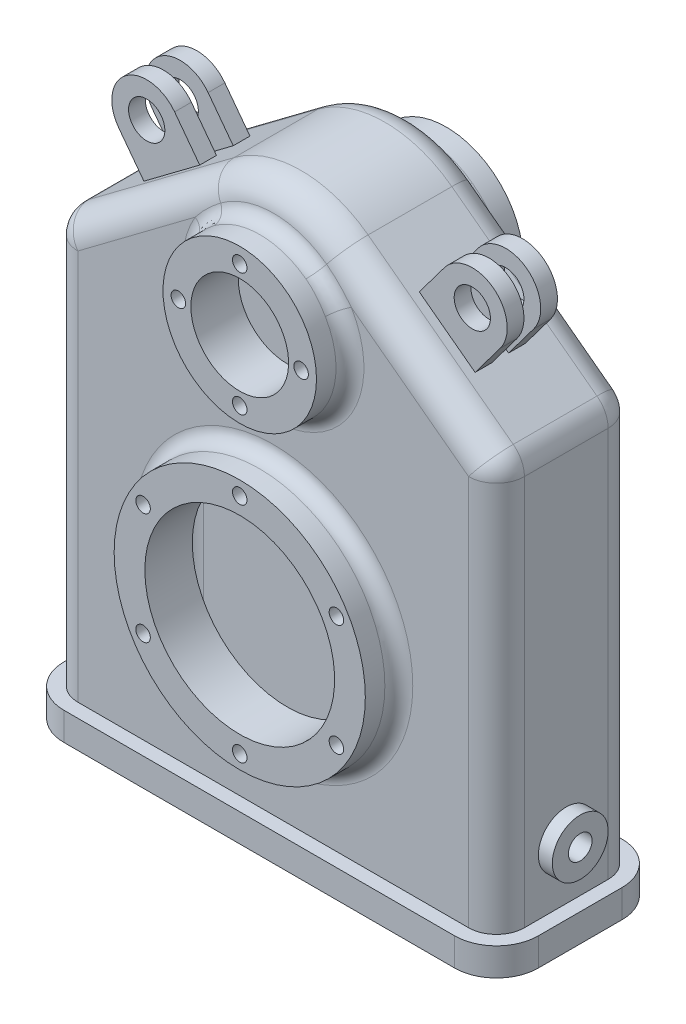
SolidWorks part; units mm, degrees
ref_plane "Front Plane" through (0, 0, 0) normal (0, 0, 1) x (1, 0, 0)
ref_plane "Top Plane" through (0, 0, 0) normal (0, 1, 0) x (1, 0, 0)
ref_plane "Right Plane" through (0, 0, 0) normal (1, 0, 0) x (0, 0, -1)
sketch "Sketch1" plane through (0, 0, 0) normal (0, 1, 0) x (1, 0, 0)
  line L1 (15, 0) -> (155, 0)
  line L2 (0, 15) -> (0, 45)
  line L3 (15, 60) -> (155, 60)
  line L4 (170, 15) -> (170, 45)
  arc A0 (155, 0) -> (170, 15) centre (155, 15) ccw
  arc A1 (0, 45) -> (15, 60) centre (15, 45) cw
  arc A2 (155, 60) -> (170, 45) centre (155, 45) cw
  arc A3 (15, 0) -> (0, 15) centre (15, 15) cw
  point P7 (170, 0)
  point P10 (0, 60)
  point P15 (0, 0)
  dimension "D3" = 15
  dimension "D1" = 170
  dimension "D2" = 60
extrude "Boss-Extrude1" add sketch "Sketch1" along normal blind 10
ref_plane "Plane1" through (0, 0, -30) normal (0, 0, 1) x (1, 0, 0)
sketch "Sketch2" plane through (0, 0, -30) normal (0, 0, 1) x (1, 0, 0)
  line L0 (5, 10) -> (165, 10)
  line L1 (15, 10) -> (0, 10) construction
  line L2 (170, 10) -> (155, 10) construction
  line L3 (165, 10) -> (165, 150)
  line L5 (5, 150) -> (5, 10)
  line L6 (0, 10) -> (0, 0) construction
  line L7 (9, 158) -> (61, 197)
  line L8 (109, 197) -> (161, 158)
  arc A0 (109, 197) -> (61, 197) centre (85, 165) ccw
  arc A1 (165, 150) -> (161, 158) centre (155, 150) ccw
  arc A2 (5, 150) -> (9, 158) centre (15, 150) cw
  point P12 (0, 0)
  point P20 (0, 0)
  dimension "D3" = 80
  dimension "D6" = 10
  dimension "D1" = 160
  dimension "D2" = 5
  dimension "D4" = 165
  dimension "D5" = 85
  dimension "D7" = 150
extrude "Boss-Extrude2" add sketch "Sketch2" along normal mid plane 50
fillet "Fillet1" radius 10 14 edges at (165, 80, -55) (163.9443, 154.4721, -55) (135, 177.5, -55) (85, 205, -55) (35, 177.5, -55) (6.0557, 154.4721, -55) (165, 80, -5) (163.9443, 154.4721, -5) (135, 177.5, -5) (85, 205, -5) (35, 177.5, -5) (6.0557, 154.4721, -5) (5, 80, -55) (5, 80, -5)
sketch "Sketch3" plane through (0, 0, -30) normal (0, 0, 1) x (1, 0, 0)
  line L0 (10, 0) -> (10, 150)
  line L1 (0, 0) -> (15, 0) construction
  line L3 (160, 150) -> (160, 0)
  line L4 (155, 0) -> (170, 0) construction
  line L5 (160, 0) -> (10, 0)
  line L6 (165, 10) -> (165, 150) construction
  line L7 (5, 150) -> (5, 10) construction
  line L8 (12, 154) -> (64, 193)
  line L9 (106, 193) -> (158, 154)
  line L10 (161, 158) -> (109, 197) construction
  arc A0 (106, 193) -> (64, 193) centre (85, 165) ccw
  arc A1 (158, 154) -> (160, 150) centre (155, 150) cw
  arc A2 (103, 189) -> (67, 189) centre (85, 165) ccw construction
  arc A3 (10, 150) -> (12, 154) centre (15, 150) cw
  point P1 (0, 0)
  point P25 (0, 0)
  dimension "D1" = 70
  dimension "D4" = 5
  dimension "D2" = 5
  dimension "D3" = 5
extrude "Cut-Extrude1" cut sketch "Sketch3" against normal mid plane 40
sketch "Sketch4" plane through (0, 0, -5) normal (0, 0, 1) x (1, 0, 0)
  circle A0 centre (85, 165) radius 27.5
  circle A1 centre (85, 75) radius 45
  point P4 (0, 0)
  point P5 (0, 0)
  dimension "D2" = 55
  dimension "D3" = 90
  dimension "D1" = 85
  dimension "D4" = 75
  dimension "D5" = 90
extrude "Boss-Extrude3" add sketch "Sketch4" along normal blind 12
sketch "Sketch9" plane through (0, 0, -55) normal (0, 0, -1) x (-1, 0, 0)
  circle A0 centre (-85, 75) radius 45 construction
  circle A1 centre (-85, 165) radius 27.5 construction
  circle A2 centre (-85, 75) radius 45
  circle A3 centre (-85, 165) radius 27.5
extrude "Boss-Extrude4" add sketch "Sketch9" along normal blind 12
sketch "Sketch10" plane through (0, 0, -67) normal (0, 0, -1) x (-1, 0, 0)
  circle A0 centre (-85, 165) radius 17.5
  circle A1 centre (-85, 75) radius 34
  dimension "D1" = 68
  dimension "D2" = 35
extrude "Cut-Extrude2" cut sketch "Sketch10" against normal through all
fillet "Fillet2" radius 5 1 edges at (130, 75, -55)
fillet "Fillet3" radius 5 2 edges at (112.5, 165, -55) (85, 195, -55)
fillet "Fillet4" radius 5 2 edges at (112.5, 165, -5) (85, 195, -5)
fillet "Fillet5" radius 5 1 edges at (130, 75, -5)
ref_plane "Plane2" through (0, 0, -24) normal (0, 0, -1) x (-1, 0, 0)
sketch "Sketch11" plane through (0, 0, -24) normal (0, 0, -1) x (-1, 0, 0)
  line L0 (-153.3333, 182.5) -> (-144.3333, 170.5)
  line L1 (-161, 158) -> (-109, 197) construction
  line L2 (-133.3333, 197.5) -> (-124.3333, 185.5)
  line L3 (-124.3333, 185.5) -> (-144.3333, 170.5)
  line L4 (-36.6667, 197.5) -> (-45.6667, 185.5)
  line L5 (-61, 197) -> (-9, 158) construction
  line L6 (-16.6667, 182.5) -> (-25.6667, 170.5)
  line L7 (-45.6667, 185.5) -> (-25.6667, 170.5)
  arc A0 (-133.3333, 197.5) -> (-153.3333, 182.5) centre (-143.3333, 190) ccw
  arc A1 (-16.6667, 182.5) -> (-36.6667, 197.5) centre (-26.6667, 190) ccw
  circle A2 centre (-143.3333, 190) radius 6.5
  circle A3 centre (-26.6667, 190) radius 6.5
  dimension "D5" = 25
  dimension "D6" = 25
  dimension "D10" = 13
  dimension "D11" = 13
  dimension "D1" = 90
  dimension "D2" = 90
  dimension "D3" = 90
  dimension "D4" = 90
  dimension "D7" = 15
  dimension "D8" = 15
  dimension "D9" = 190
extrude "Boss-Extrude6" add sketch "Sketch11" against normal blind 6
ref_plane "Plane4" through (0, 0, -30) normal (0, 0, 1) x (1, 0, 0)
sketch "Sketch13" plane through (0, 0, -30) normal (0, 0, 1) x (1, 0, 0)
  line L0 (133.3333, 197.5) -> (124.3333, 185.5) construction
  line L1 (124.3333, 185.5) -> (144.3333, 170.5) construction
  line L2 (144.3333, 170.5) -> (153.3333, 182.5) construction
  line L3 (16.6667, 182.5) -> (25.6667, 170.5) construction
  line L4 (25.6667, 170.5) -> (45.6667, 185.5) construction
  line L5 (45.6667, 185.5) -> (36.6667, 197.5) construction
  line L6 (133.3333, 197.5) -> (124.3333, 185.5)
  line L7 (124.3333, 185.5) -> (144.3333, 170.5)
  line L8 (144.3333, 170.5) -> (153.3333, 182.5)
  line L9 (16.6667, 182.5) -> (25.6667, 170.5)
  line L10 (25.6667, 170.5) -> (45.6667, 185.5)
  line L11 (45.6667, 185.5) -> (36.6667, 197.5)
  arc A0 (153.3333, 182.5) -> (133.3333, 197.5) centre (143.3333, 190) ccw construction
  arc A1 (36.6667, 197.5) -> (16.6667, 182.5) centre (26.6667, 190) ccw construction
  arc A2 (153.3333, 182.5) -> (133.3333, 197.5) centre (143.3333, 190) ccw
  arc A3 (36.6667, 197.5) -> (16.6667, 182.5) centre (26.6667, 190) ccw
extrude "Boss-Extrude7" add sketch "Sketch13" against normal blind 6
sketch "Sketch14" plane through (0, 0, -36) normal (0, 0, -1) x (-1, 0, 0)
  circle A0 centre (-26.6667, 190) radius 6.5
  circle A1 centre (-143.3333, 190) radius 6.5
extrude "Cut-Extrude3" cut sketch "Sketch14" against normal blind 6
fillet "Fillet10" radius 5 7 edges at (160, 75, -50) (159.4721, 152.2361, -50) (132, 173.5, -50) (85, 200, -50) (38, 173.5, -50) (10.5279, 152.2361, -50) (10, 75, -50)
fillet "Fillet11" radius 5 7 edges at (10, 75, -10) (10.5279, 152.2361, -10) (38, 173.5, -10) (85, 200, -10) (132, 173.5, -10) (159.4721, 152.2361, -10) (160, 75, -10)
sketch "Sketch15" plane through (165, 0, 0) normal (1, 0, 0) x (0, 0, -1)
  circle A0 centre (30, 30) radius 10
  dimension "D1" = 30
  dimension "D2" = 30
extrude "Boss-Extrude8" add sketch "Sketch15" along normal blind 5
sketch "Sketch16" plane through (170, 0, 0) normal (1, 0, 0) x (0, 0, -1)
  point P0 (30, 30)
hole_wizard "Tap Drill for M10 Tap1" positions "3DSketch8" profile "Sketch24" hole size "M10" standard "DIN"
sketch3d "3DSketch8"
  point P0 (170, 30, -30)
sketch "Sketch24" plane through (170, 30, -30) normal (0, 1, 0) x (0, 0, -1)
  line L0 (0, 0) -> (0, 50)
  line L1 (0, 50) -> (4.25, 47.4463)
  line L2 (4.25, 47.4463) -> (4.25, 0)
  line L5 (4.25, 0) -> (0, 0)
  line L10 (0, 50) -> (-4.25, 47.4463) construction
  line L11 (0, -6.35) -> (0, 107.95) construction
  dimension "Hole Dia." = 8.5
  dimension "Hole Depth" = 50
  dimension "Drill Angle" = 118
sketch "Sketch25" plane through (0, 0, -67) normal (0, 0, -1) x (-1, 0, 0)
  circle A0 centre (-85, 75) radius 40 construction
  circle A1 centre (-85, 165) radius 22 construction
  point P3 (-85, 187)
  point P7 (-85, 115)
  point P10 (-63, 165)
  point P11 (-85, 143)
  point P12 (-107, 165)
  point P13 (-85, 165)
  point P14 (-50.359, 95)
  point P15 (-50.359, 55)
  point P16 (-85, 35)
  point P17 (-119.641, 55)
  point P18 (-119.641, 95)
  point P19 (-85, 75)
  dimension "D1" = 4
  dimension "D2" = 6
sketch "Sketch27" plane through (0, 0, 7) normal (0, 0, 1) x (1, 0, 0)
  circle A0 centre (85, 75) radius 40 construction
  circle A1 centre (85, 165) radius 27.5
  circle A2 centre (85, 165) radius 27.5
  circle A3 centre (85, 165) radius 22 construction
  circle A4 centre (85, 75) radius 40 construction
  circle A5 centre (85, 165) radius 22 construction
  point P9 (85, 187)
  point P10 (85, 115)
  point P13 (107, 165)
  point P14 (85, 143)
  point P15 (63, 165)
  point P16 (85, 165)
  point P18 (119.641, 95)
  point P19 (119.641, 55)
  point P20 (85, 35)
  point P21 (50.359, 55)
  point P22 (50.359, 95)
  point P23 (85, 75)
  dimension "D1" = 0
  dimension "D2" = 4
  dimension "D3" = 6
hole_wizard "Tap Drill for M5 Helicoil1" positions "3DSketch9" profile "Sketch28" hole size "M5x0.8" standard "DIN"
sketch3d "3DSketch9"
  point P0 (85, 187, 7)
  point P3 (107, 165, 7)
  point P6 (85, 143, -67)
  point P9 (63, 165, -67)
  point P12 (85, 115, -67)
  point P15 (119.641, 95, -67)
  point P18 (119.641, 55, -67)
  point P21 (85, 35, -67)
  point P24 (50.359, 55, -67)
  point P27 (50.359, 95, -67)
  point P30 (-9.8, 169.5694, 0)
  point P32 (85, 115, 7)
  point P35 (50.359, 95, 7)
  point P38 (50.359, 55, 7)
  point P41 (85, 35, 7)
  point P44 (119.641, 55, 7)
  point P47 (119.641, 95, 7)
  point P50 (107, 165, -67)
  point P53 (85, 187, -67)
  point P56 (85, 143, 7)
  point P59 (63, 165, 7)
sketch "Sketch28" plane through (85, 187, 7) normal (1, 0, 0) x (0, -1, 0)
  line L0 (0, 0) -> (0, 9.5622)
  line L1 (0, 9.5622) -> (2.6, 8)
  line L2 (2.6, 8) -> (2.6, 0)
  line L5 (2.6, 0) -> (0, 0)
  line L10 (0, 9.5622) -> (-2.6, 8) construction
  line L11 (0, -6.35) -> (0, 107.95) construction
  dimension "Hole Dia." = 5.2
  dimension "Hole Depth" = 8
  dimension "Drill Angle" = 118
sketch "Sketch29" plane through (0, 0, 0) normal (0, -1, 0) x (1, 0, 0)
  line L0 (85, -15) -> (85, -45) construction
  line L1 (0, -45) -> (0, -15) construction
  line L2 (10, -45) -> (10, -15) construction
  point P0 (45, -5)
  point P1 (125, -5)
  point P2 (125, -55)
  point P3 (45, -55)
  point P4 (5, -30)
  point P5 (165, -30)
  point P12 (10, -30)
  point P14 (0, 0)
  dimension "D1" = 80
  dimension "D2" = 40
  dimension "D3" = 160
  dimension "D4" = 5
  dimension "D5" = 50
  dimension "D6" = 25
hole_wizard "Tap Drill for M5 Helicoil2" positions "3DSketch10" profile "Sketch30" hole size "M5x0.8" standard "DIN"
sketch3d "3DSketch10"
  point P0 (5, 0, -30)
  point P3 (45, 0, -5)
  point P6 (45, 0, -55)
  point P9 (125, 0, -55)
  point P12 (165, 0, -30)
  point P15 (125, 0, -5)
sketch "Sketch30" plane through (5, 0, -30) normal (1, 0, 0) x (0, 0, -1)
  line L0 (0, 0) -> (0, 7.5622)
  line L1 (0, 7.5622) -> (2.6, 6)
  line L2 (2.6, 6) -> (2.6, 0)
  line L5 (2.6, 0) -> (0, 0)
  line L10 (0, 7.5622) -> (-2.6, 6) construction
  line L11 (0, -6.35) -> (0, 107.95) construction
  dimension "Hole Dia." = 5.2
  dimension "Hole Depth" = 6
  dimension "Drill Angle" = 118
